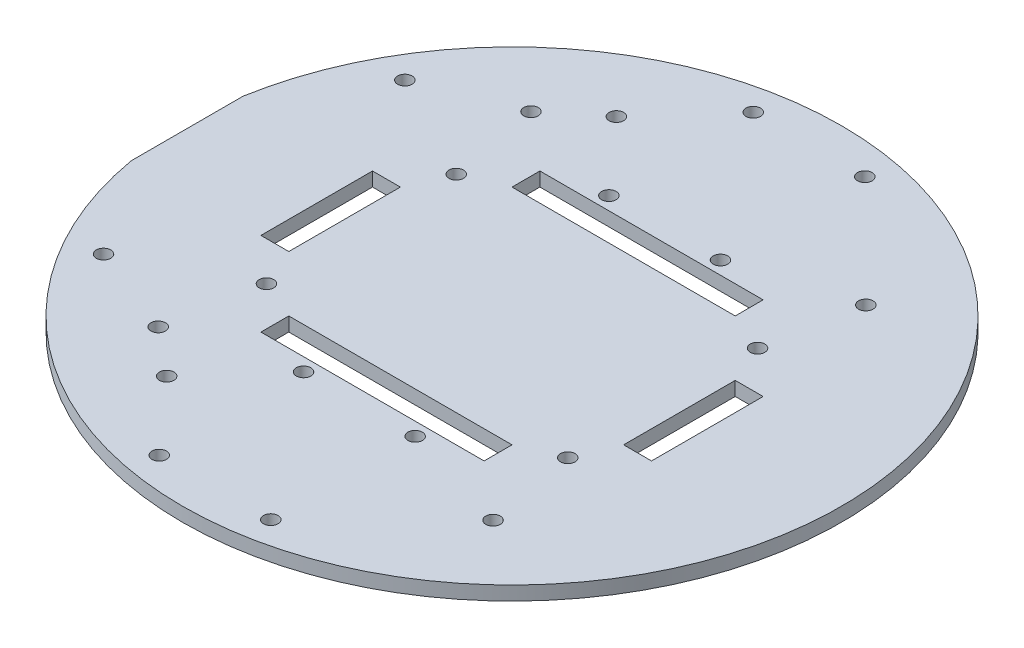
SolidWorks part; units mm, degrees
material "Acrylic (Medium-high impact)"
ref_plane "Front Plane" through (0, 0, 0) normal (0, 0, 1) x (1, 0, 0)
ref_plane "Top Plane" through (0, 0, 0) normal (0, 1, 0) x (1, 0, 0)
ref_plane "Right Plane" through (0, 0, 0) normal (1, 0, 0) x (0, 0, -1)
sketch "Sketch1" plane through (0, 0, 0) normal (0, 1, 0) x (1, 0, 0)
  line L0 (-73.9169, 12.7) -> (-73.9169, -12.7)
  line L1 (-73.9169, 12.7) -> (-73.9169, -12.7) construction
  line L2 (-34.29, 21.59) -> (34.29, 21.59) construction
  line L3 (34.29, 21.59) -> (34.29, -21.59) construction
  line L4 (34.29, -21.59) -> (-34.29, -21.59) construction
  line L5 (-34.29, -21.59) -> (-34.29, 21.59) construction
  line L6 (0, 21.59) -> (0, 75) construction
  line L7 (34.29, 0) -> (75, 0) construction
  line L8 (0, -25.4) -> (0, -21.59) construction
  line L9 (-34.29, 0) -> (-38.1, 0) construction
  line L10 (-25.4, 31.75) -> (25.4, 31.75)
  line L11 (-25.4, 31.75) -> (-25.4, 25.4)
  line L12 (-25.4, 25.4) -> (25.4, 25.4)
  line L13 (25.4, 31.75) -> (25.4, 25.4)
  line L14 (38.1, 12.7) -> (44.45, 12.7)
  line L15 (38.1, 12.7) -> (38.1, -12.7)
  line L16 (38.1, -12.7) -> (44.45, -12.7)
  line L17 (44.45, 12.7) -> (44.45, -12.7)
  line L18 (25.4, -25.4) -> (-25.4, -25.4)
  line L19 (25.4, -25.4) -> (25.4, -31.75)
  line L20 (25.4, -31.75) -> (-25.4, -31.75)
  line L21 (-25.4, -25.4) -> (-25.4, -31.75)
  line L22 (-44.45, -12.7) -> (-38.1, -12.7)
  line L23 (-44.45, -12.7) -> (-44.45, 12.7)
  line L24 (-44.45, 12.7) -> (-38.1, 12.7)
  line L25 (-38.1, -12.7) -> (-38.1, 12.7)
  line L26 (38.1, 12.7) -> (34.29, 12.7) construction
  line L27 (25.4, 25.4) -> (25.4, 21.59) construction
  line L28 (-24.25, -37.9184) -> (24.25, -37.9184) construction
  line L29 (24.25, -37.9184) -> (24.25, -64.4184) construction
  line L30 (-12.7, -37.9184) -> (-12.7, -34.7434) construction
  line L31 (24.25, -64.4184) -> (-24.25, -64.4184) construction
  line L32 (-24.25, -64.4184) -> (-24.25, -37.9184) construction
  line L33 (-24.25, -64.4184) -> (-26.4232, -70.1913) construction
  line L34 (24.25, -64.4184) -> (26.4232, -70.1913) construction
  line L35 (-24.25, -37.9184) -> (-24.25, -31.75) construction
  line L36 (0, -37.9184) -> (0, -64.4184) construction
  line L38 (-27.425, -51.1684) -> (-24.25, -51.1684) construction
  line L39 (-12.7, -67.5934) -> (-12.7, -64.4184) construction
  arc A0 (-73.9169, -12.7) -> (-73.9169, 12.7) centre (0, 0) ccw
  arc A1 (55.356, -50.6035) -> (55.356, 50.6035) centre (0, 0) ccw construction
  circle A2 centre (-34.29, 21.59) radius 1.651
  circle A3 centre (34.29, 21.59) radius 1.651
  circle A4 centre (-34.29, -21.59) radius 1.651
  circle A5 centre (34.29, -21.59) radius 1.651
  circle A6 centre (-39.6269, 47.4285) radius 1.651 construction
  circle A7 centre (38.1, -42.418) radius 1.651
  circle A8 centre (-38.1, -42.418) radius 1.651
  circle A9 centre (-58.6769, -34.29) radius 1.651
  circle A10 centre (-58.6769, 34.29) radius 1.651
  circle A11 centre (-38.1, 42.418) radius 1.651
  circle A12 centre (38.1, 42.418) radius 1.651
  circle A13 centre (51.7494, -47.4285) radius 1.651 construction
  circle A14 centre (12.7, -67.5934) radius 1.651
  circle A15 centre (12.7, -34.7434) radius 1.651
  circle A16 centre (12.7, 34.7434) radius 1.651
  circle A17 centre (12.7, 67.5934) radius 1.651
  circle A22 centre (-27.425, -51.1684) radius 1.651
  circle A23 centre (-12.7, -34.7434) radius 1.651
  circle A24 centre (-12.7, -67.5934) radius 1.651
  circle A25 centre (-12.7, 67.5934) radius 1.651
  circle A26 centre (-27.425, 51.1684) radius 1.651
  circle A27 centre (-12.7, 34.7434) radius 1.651
  dimension "D11" = 3.302
  dimension "D1" = 68.58
  dimension "D2" = 43.18
  dimension "D3" = 3.81
  dimension "D4" = 6.35
  dimension "D5" = 50.8
  dimension "D6" = 25.4
  dimension "D7" = 48.5
  dimension "D8" = 26.5
  dimension "D9" = 12.7
  dimension "D10" = 3.175
extrude "Boss-Extrude1" add sketch "Sketch1" along normal blind 3.175
sketch "Sketch2" plane through (0, 3.175, 0) normal (0, 1, 0) x (1, 0, 0)
  line L0 (55.1757, 50.8) -> (55.1757, -50.8) construction
  arc A0 (-73.9169, -12.7) -> (-73.9169, 12.7) centre (0, 0) ccw construction
  text T0 "Sean Reidy, Klyde Breitton, Nick LaBarbera" font "Mufferaw" height in points 12
  dimension "D1" = 101.6
